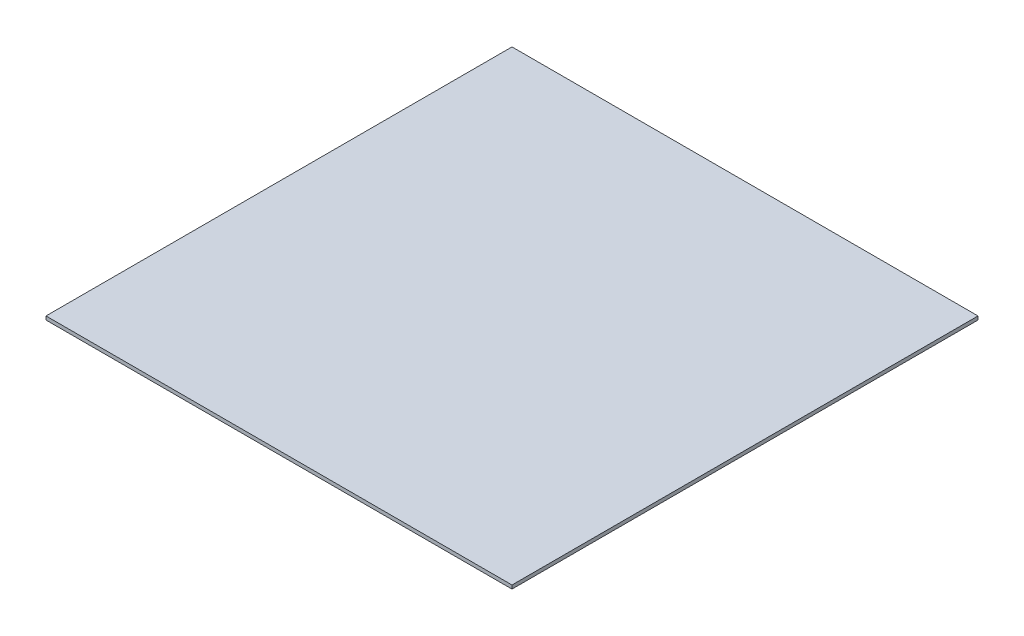
SolidWorks part; units mm, degrees
ref_plane "前视基准面" through (0, 0, 0) normal (0, 0, 1) x (1, 0, 0)
ref_plane "上视基准面" through (0, 0, 0) normal (0, 1, 0) x (1, 0, 0)
ref_plane "右视基准面" through (0, 0, 0) normal (1, 0, 0) x (0, 0, -1)
sketch "草图1" plane through (0, 0, 0) normal (0, 1, 0) x (1, 0, 0)
  line L0 (-130, 130) -> (130, -130) construction
  line L1 (-130, -130) -> (130, -130)
  line L2 (-130, -130) -> (-130, 130)
  line L3 (-130, 130) -> (130, 130)
  line L4 (130, -130) -> (130, 130)
  line L5 (130, 130) -> (-130, -130) construction
  point P5 (0, 0)
  dimension "D1" = 260
  dimension "D2" = 260
extrude "网" add sketch "草图1" along normal blind 2 contours L2 L3 L4 L1
